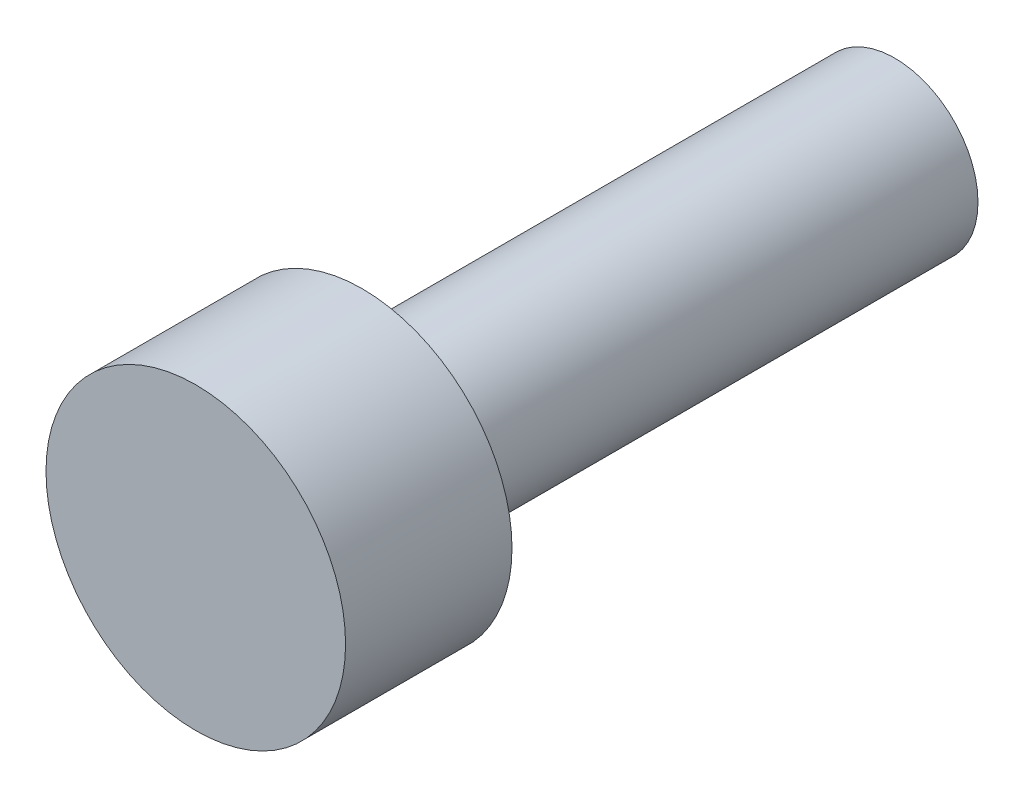
SolidWorks part; units mm, degrees
ref_plane "Front Plane" through (0, 0, 0) normal (0, 0, 1) x (1, 0, 0)
ref_plane "Top Plane" through (0, 0, 0) normal (0, 1, 0) x (1, 0, 0)
ref_plane "Right Plane" through (0, 0, 0) normal (1, 0, 0) x (0, 0, -1)
sketch "Sketch1" plane through (0, 0, 0) normal (0, 0, 1) x (1, 0, 0)
  circle A0 centre (0, 0) radius 1.25
extrude "Thread_Envelope" add sketch "Sketch1" along normal blind 8 from offset 8
sketch "Sketch2" plane through (0, 0, 0) normal (0, 0, 1) x (1, 0, 0)
  circle A0 centre (0, 0) radius 2.25
extrude "Head_Envelope" add sketch "Sketch2" along normal blind 2.5
